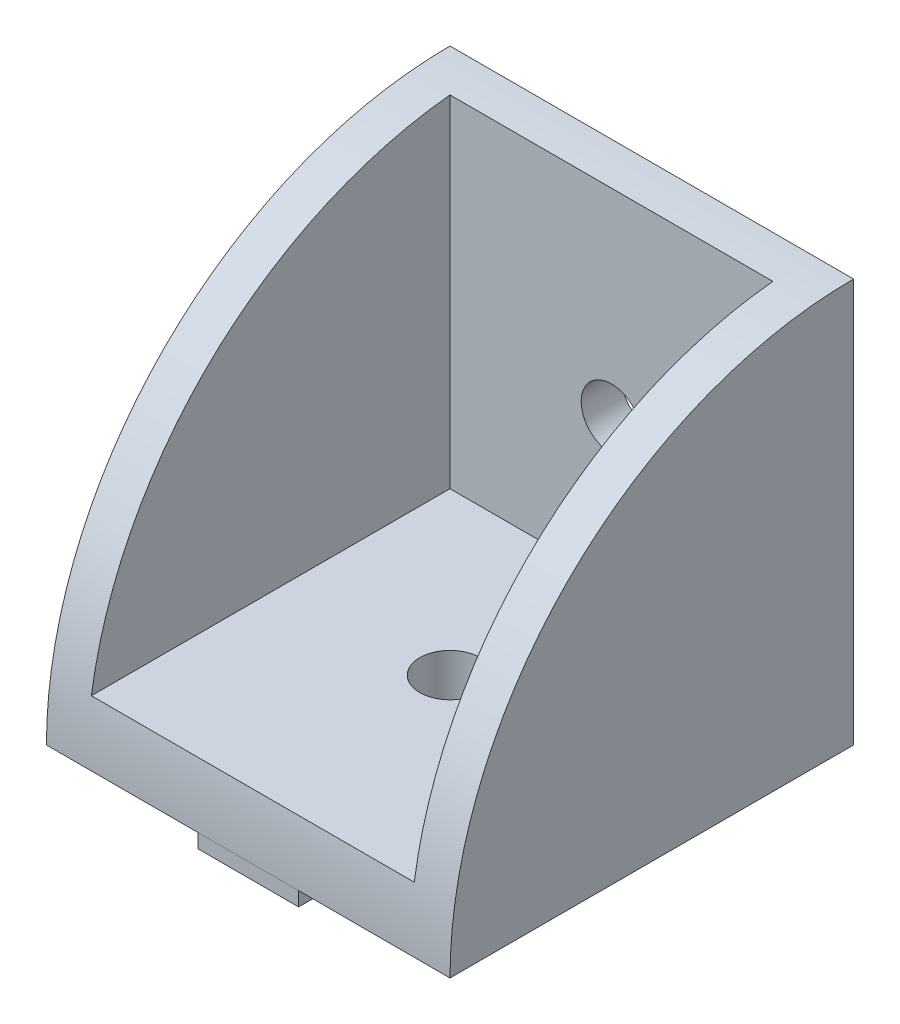
SolidWorks part; units mm, degrees
ref_plane "Спереди" through (0, 0, 0) normal (0, 0, 1) x (1, 0, 0)
ref_plane "Сверху" through (0, 0, 0) normal (0, 1, 0) x (1, 0, 0)
ref_plane "Справа" through (0, 0, 0) normal (1, 0, 0) x (0, 0, -1)
sketch "Эскиз1" plane through (0, 0, 0) normal (0, 0, 1) x (1, 0, 0)
  line L1 (0, 0) -> (20, 0)
  line L2 (0, 0) -> (0, 20)
  line L3 (0, 20) -> (20, 20)
  line L4 (20, 0) -> (20, 20)
  dimension "D1" = 20
  dimension "D2" = 20
revolve "Повернуть1" add sketch "Эскиз1" angle 90 about L1
sketch "Эскиз2" plane through (0, 0, 0) normal (0, -1, 0) x (1, 0, 0)
  line L0 (20, 20) -> (0, 20) construction
  line L1 (2, 20) -> (18, 20)
  line L2 (2, 20) -> (2, 2)
  line L3 (2, 2) -> (18, 2)
  line L4 (18, 20) -> (18, 2)
  line L5 (0, 0) -> (20, 0) construction
  line L6 (0, 20) -> (0, 0) construction
  line L7 (20, 0) -> (20, 20) construction
  dimension "D1" = 2
  dimension "D2" = 2
  dimension "D3" = 2
extrude "Вырез-Вытянуть1" cut sketch "Эскиз2" against normal blind 30
sketch "Эскиз3" plane through (0, 0, 0) normal (0, -1, 0) x (1, 0, 0)
  line L1 (2, 2) -> (18, 2)
  line L2 (2, 2) -> (2, 20)
  line L3 (2, 20) -> (18, 20)
  line L4 (18, 2) -> (18, 20)
extrude "Бобышка-Вытянуть1" add sketch "Эскиз3" against normal blind 3
sketch "Эскиз4" plane through (0, 0, 0) normal (-1, 0, 0) x (0, 0, 1)
  circle A0 centre (0, 0) radius 20
  circle A1 centre (0, 0) radius 21
  dimension "D1" = 1
extrude "Вырез-Вытянуть2" cut sketch "Эскиз4" against normal through all
sketch "Эскиз5" plane through (0, 0, 0) normal (0, 0, -1) x (-1, 0, 0)
  line L0 (0, 0) -> (-20, 0) construction
  line L1 (-20, 0) -> (-20, 20) construction
  circle A0 centre (-10, 10) radius 1.5
  dimension "D1" = 3
  dimension "D3" = 10
  dimension "D2" = 10
extrude "Вырез-Вытянуть3" cut sketch "Эскиз5" against normal through all
sketch "Эскиз6" plane through (0, 0, 0) normal (0, -1, 0) x (1, 0, 0)
  line L0 (20, 20) -> (0, 20) construction
  line L1 (7.5, 20) -> (12.5, 20)
  line L2 (7.5, 20) -> (7.5, 0)
  line L3 (7.5, 0) -> (12.5, 0)
  line L4 (12.5, 20) -> (12.5, 0)
  line L5 (0, 0) -> (20, 0) construction
  point P8 (10, 20)
  dimension "D1" = 5
  dimension "D2" = 10
extrude "Бобышка-Вытянуть2" add sketch "Эскиз6" along normal blind 0.7 contours L2 L3 L4 L1
sketch "Эскиз7" plane through (0, -0.7, 0) normal (0, -1, 0) x (1, 0, 0)
  line L0 (12.5, 20) -> (12.5, 0) construction
  line L1 (7.5, 20) -> (12.5, 20) construction
  circle A0 centre (10, 10) radius 1.5
  dimension "D1" = 3
  dimension "D2" = 2.5
  dimension "D3" = 10
extrude "Вырез-Вытянуть4" cut sketch "Эскиз7" against normal blind 100
